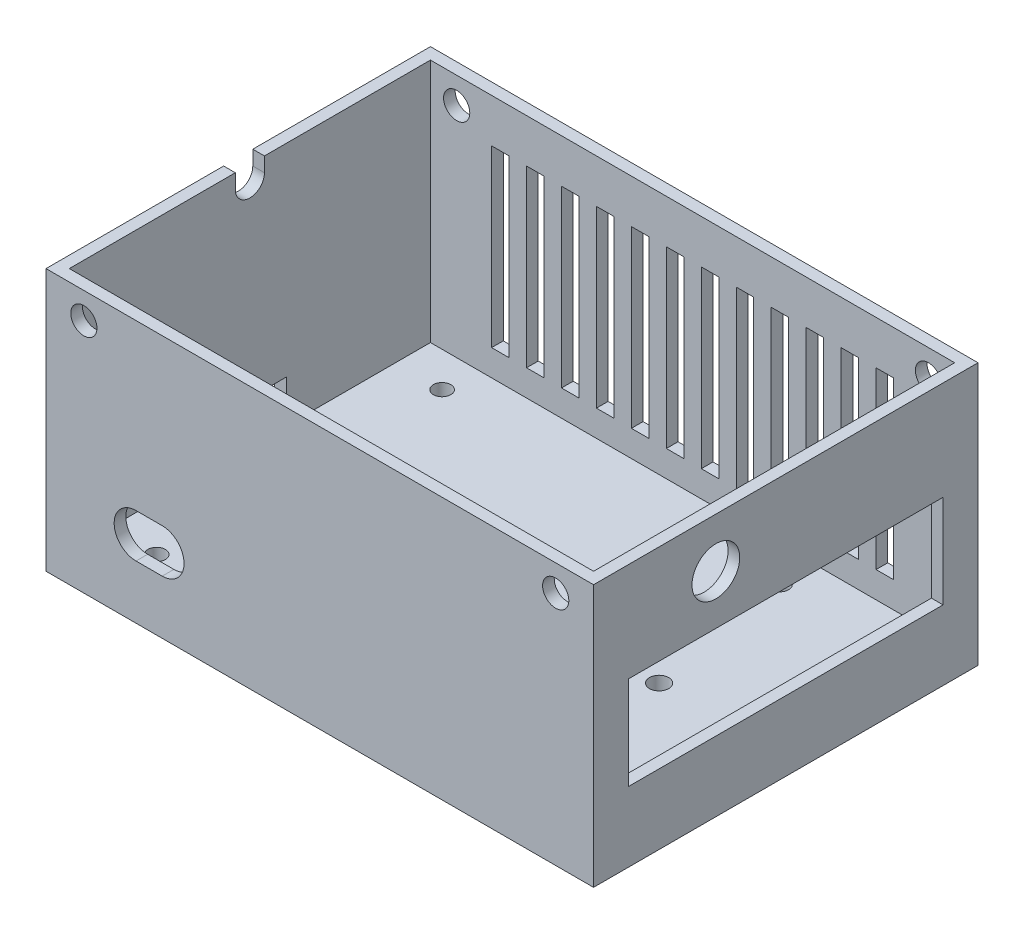
SolidWorks part; units mm, degrees
ref_plane "Front Plane" through (0, 0, 0) normal (0, 0, 1) x (1, 0, 0)
ref_plane "Top Plane" through (0, 0, 0) normal (0, 1, 0) x (1, 0, 0)
ref_plane "Right Plane" through (0, 0, 0) normal (1, 0, 0) x (0, 0, -1)
sketch "Sketch1" plane through (0, 0, 0) normal (0, 1, 0) x (1, 0, 0)
  line L1 (-45, -31) -> (45, -31)
  line L2 (-45, -31) -> (-45, 31)
  line L3 (-45, 31) -> (45, 31)
  line L4 (45, -31) -> (45, 31)
  line L5 (-45, -31) -> (45, 31) construction
  line L6 (-45, 31) -> (45, -31) construction
  point P0 (0, 0)
  dimension "D1" = 90
  dimension "D2" = 62
extrude "Boss-Extrude1" add sketch "Sketch1" along normal blind 3
sketch "Sketch2" plane through (0, 3, 0) normal (0, 1, 0) x (1, 0, 0)
  line L0 (-45, -31) -> (45, -31) construction
  line L1 (-45, 31) -> (-45, -31) construction
  circle A0 centre (-37, -24) radius 1.5
  circle A1 centre (21, -24) radius 1.5
  circle A2 centre (21, 25) radius 1.5
  circle A3 centre (-37, 25) radius 1.5
  dimension "D1" = 3
  dimension "D2" = 7
  dimension "D3" = 8
  dimension "D5" = 58
  dimension "D6" = 2
  dimension "D7" = 49
  dimension "D4" = 2
extrude "Cut-Extrude1" cut sketch "Sketch2" against normal up to next
sketch "Sketch3" plane through (0, 0, 0) normal (0, 1, 0) x (1, 0, 0)
  line L1 (-45, -31) -> (45, -31)
  line L2 (-45, -31) -> (-45, 31)
  line L3 (-45, 31) -> (45, 31)
  line L4 (45, -31) -> (45, 31)
  line L5 (-45, -31) -> (45, 31) construction
  line L6 (-45, 31) -> (45, -31) construction
  line L7 (-47, -33) -> (47, -33)
  line L8 (-47, -33) -> (-47, 33)
  line L9 (-47, 33) -> (47, 33)
  line L10 (47, -33) -> (47, 33)
  line L11 (-47, -33) -> (47, 33) construction
  line L12 (-47, 33) -> (47, -33) construction
  point P0 (0, 0)
  point P7 (0, 0)
  dimension "D1" = 2
  dimension "D2" = 2
extrude "Boss-Extrude2" add sketch "Sketch3" along normal blind 45
sketch "Sketch4" plane through (-45, 0, 0) normal (1, 0, 0) x (0, 0, -1)
  line L0 (0, 3) -> (0, 45) construction
  line L1 (31, 3) -> (-31, 3) construction
  line L2 (31, 45) -> (-31, 45) construction
  line L4 (-6.25, 10.25) -> (6.25, 10.25)
  line L5 (-6.25, 10.25) -> (-6.25, 7.75)
  line L6 (-6.25, 7.75) -> (6.25, 7.75)
  line L7 (6.25, 10.25) -> (6.25, 7.75)
  line L8 (-6.25, 10.25) -> (6.25, 7.75) construction
  line L9 (-6.25, 7.75) -> (6.25, 10.25) construction
  point P6 (0, 9)
  dimension "D1" = 6
  dimension "D2" = 2.5
  dimension "D3" = 12.5
extrude "Cut-Extrude2" cut sketch "Sketch4" against normal up to next
sketch "Sketch5" plane through (0, 0, 31) normal (0, 0, -1) x (-1, 0, 0)
  line L0 (29.3, 3) -> (29.3, 45) construction
  line L1 (45, 3) -> (-45, 3) construction
  line L2 (45, 45) -> (-45, 45) construction
  line L3 (45, 45) -> (45, 3) construction
  line L4 (31.55, 13) -> (27.05, 13) construction
  line L5 (31.55, 9.25) -> (27.05, 9.25)
  line L6 (31.55, 16.75) -> (27.05, 16.75)
  line L7 (35.3, 13) -> (23.3, 13) construction
  arc A0 (31.55, 9.25) -> (31.55, 16.75) centre (31.55, 13) ccw
  arc A1 (27.05, 16.75) -> (27.05, 9.25) centre (27.05, 13) ccw
  point P10 (29.3, 13)
  dimension "D4" = 10
  dimension "D1" = 15.7
  dimension "D2" = 7.5
  dimension "D3" = 12
extrude "Cut-Extrude3" cut sketch "Sketch5" against normal up to next
sketch "Sketch6" plane through (45, 0, 0) normal (-1, 0, 0) x (0, 0, 1)
  line L0 (0, 3) -> (0, 45) construction
  line L1 (31, 3) -> (-31, 3) construction
  line L2 (31, 45) -> (-31, 45) construction
  line L3 (31, 45) -> (31, 3) construction
  line L4 (-27, 12) -> (27, 12)
  line L5 (-27, 12) -> (-27, 28)
  line L6 (-27, 28) -> (27, 28)
  line L7 (27, 12) -> (27, 28)
  line L8 (-27, 12) -> (27, 28) construction
  line L9 (-27, 28) -> (27, 12) construction
  point P6 (0, 20)
  dimension "D1" = 9
  dimension "D2" = 16
  dimension "D3" = 4
extrude "Cut-Extrude4" cut sketch "Sketch6" against normal up to next
sketch "Sketch7" plane through (47, 0, 0) normal (1, 0, 0) x (0, 0, -1)
  line L0 (-27, 28) -> (-27, 45) construction
  line L1 (-33, 45) -> (33, 45) construction
  line L2 (-27, 36.5) -> (33, 36.5) construction
  line L3 (33, 45) -> (33, 0) construction
  circle A0 centre (-12, 36.5) radius 4.1
  dimension "D1" = 8.2
  dimension "D2" = 15
extrude "Cut-Extrude5" cut sketch "Sketch7" against normal up to next
sketch "Sketch8" plane through (0, 0, 33) normal (0, 0, 1) x (1, 0, 0)
  line L0 (-47, 45) -> (-47, 0) construction
  line L1 (-47, 45) -> (47, 45) construction
  line L2 (0, 45) -> (0, 0) construction
  line L3 (-47, 0) -> (47, 0) construction
  circle A0 centre (-40.5, 40.5) radius 2.25
  circle A1 centre (40.5, 40.5) radius 2.25
  dimension "D1" = 4.5
  dimension "D2" = 6.5
  dimension "D3" = 4.5
extrude "Cut-Extrude6" cut sketch "Sketch8" against normal through all
sketch "Sketch9" plane through (0, 3, 0) normal (0, 1, 0) x (1, 0, 0)
  line L0 (-45, 0) -> (45, 0) construction
  line L1 (-45, 31) -> (-45, -31) construction
  line L2 (45, -31) -> (45, 31) construction
  circle A1 centre (0, 0) radius 1.65
  circle A2 centre (25.25, 0) radius 1.65
  circle A3 centre (0, 0) radius 1.65
  circle A4 centre (-25.25, 0) radius 1.65
  dimension "D1" = 3.3
  dimension "D2" = 2
  dimension "D4" = 25.25
  dimension "D5" = 25.25
  dimension "D3" = 2
extrude "Cut-Extrude7" cut sketch "Sketch9" against normal through all contours A4 L0 | L0 A4 | A1 L0 | L0 A3 | L0 A2 | A2 L0
sketch "Sketch10" plane through (0, 0, -33) normal (0, 0, -1) x (-1, 0, 0)
  line L0 (0, 0) -> (0, 45) construction
  line L1 (-47, 45) -> (47, 45) construction
  line L2 (0, 22.5) -> (47, 22.5) construction
  line L3 (47, 45) -> (47, 0) construction
  line L4 (10.5, 37.5) -> (10.5, 7.5)
  line L5 (4.5, 37.5) -> (1.5, 37.5)
  line L6 (4.5, 37.5) -> (4.5, 7.5)
  line L7 (4.5, 7.5) -> (1.5, 7.5)
  line L8 (1.5, 37.5) -> (1.5, 7.5)
  line L9 (4.5, 37.5) -> (1.5, 7.5) construction
  line L10 (4.5, 7.5) -> (1.5, 37.5) construction
  line L11 (10.5, 37.5) -> (7.5, 37.5)
  line L12 (7.5, 37.5) -> (7.5, 7.5)
  line L13 (10.5, 7.5) -> (7.5, 7.5)
  line L14 (16.5, 37.5) -> (16.5, 7.5)
  line L15 (16.5, 37.5) -> (13.5, 37.5)
  line L16 (13.5, 37.5) -> (13.5, 7.5)
  line L17 (16.5, 7.5) -> (13.5, 7.5)
  line L18 (22.5, 37.5) -> (22.5, 7.5)
  line L19 (22.5, 37.5) -> (19.5, 37.5)
  line L20 (19.5, 37.5) -> (19.5, 7.5)
  line L21 (22.5, 7.5) -> (19.5, 7.5)
  line L22 (28.5, 37.5) -> (28.5, 7.5)
  line L23 (28.5, 37.5) -> (25.5, 37.5)
  line L24 (25.5, 37.5) -> (25.5, 7.5)
  line L25 (28.5, 7.5) -> (25.5, 7.5)
  line L26 (34.5, 37.5) -> (34.5, 7.5)
  line L27 (34.5, 37.5) -> (31.5, 37.5)
  line L28 (31.5, 37.5) -> (31.5, 7.5)
  line L29 (34.5, 7.5) -> (31.5, 7.5)
  line L30 (-4.5, 7.5) -> (-1.5, 7.5)
  line L31 (-1.5, 37.5) -> (-1.5, 7.5)
  line L32 (-4.5, 37.5) -> (-1.5, 37.5)
  line L33 (-4.5, 37.5) -> (-4.5, 7.5)
  line L34 (-10.5, 37.5) -> (-7.5, 37.5)
  line L35 (-7.5, 37.5) -> (-7.5, 7.5)
  line L36 (-10.5, 7.5) -> (-7.5, 7.5)
  line L37 (-10.5, 37.5) -> (-10.5, 7.5)
  line L38 (-16.5, 37.5) -> (-13.5, 37.5)
  line L39 (-13.5, 37.5) -> (-13.5, 7.5)
  line L40 (-16.5, 7.5) -> (-13.5, 7.5)
  line L41 (-16.5, 37.5) -> (-16.5, 7.5)
  line L42 (-22.5, 37.5) -> (-19.5, 37.5)
  line L43 (-19.5, 37.5) -> (-19.5, 7.5)
  line L44 (-22.5, 7.5) -> (-19.5, 7.5)
  line L45 (-22.5, 37.5) -> (-22.5, 7.5)
  line L46 (-28.5, 37.5) -> (-25.5, 37.5)
  line L47 (-25.5, 37.5) -> (-25.5, 7.5)
  line L48 (-28.5, 7.5) -> (-25.5, 7.5)
  line L49 (-28.5, 37.5) -> (-28.5, 7.5)
  line L50 (-34.5, 37.5) -> (-31.5, 37.5)
  line L51 (-31.5, 37.5) -> (-31.5, 7.5)
  line L52 (-34.5, 7.5) -> (-31.5, 7.5)
  line L53 (-34.5, 37.5) -> (-34.5, 7.5)
  point P9 (3, 22.5)
  dimension "D1" = 3
  dimension "D2" = 1.5
  dimension "D3" = 30
  dimension "D5" = 3
  dimension "D4" = 6
extrude "Cut-Extrude8" cut sketch "Sketch10" against normal up to next
sketch "Sketch11" plane through (-47, 0, 0) normal (-1, 0, 0) x (0, 0, 1)
  line L0 (0, 47.5) -> (0, 42.5) construction
  line L1 (-33, 45) -> (33, 45) construction
  line L2 (2.5, 47.5) -> (2.5, 42.5)
  line L3 (-2.5, 47.5) -> (-2.5, 42.5)
  arc A0 (2.5, 47.5) -> (-2.5, 47.5) centre (0, 47.5) ccw
  arc A1 (-2.5, 42.5) -> (2.5, 42.5) centre (0, 42.5) ccw
  point P5 (0, 45)
  dimension "D1" = 2.5
  dimension "D2" = 5
extrude "Cut-Extrude9" cut sketch "Sketch11" against normal up to next
